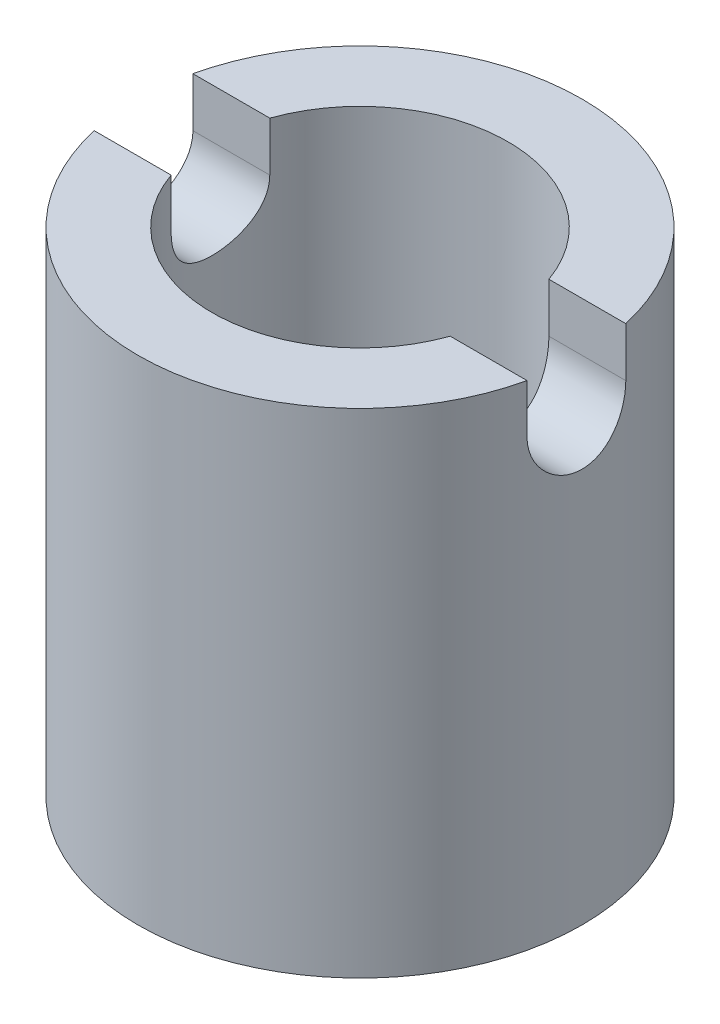
SolidWorks part; units mm, degrees
ref_plane "正面" through (0, 0, 0) normal (0, 0, 1) x (1, 0, 0)
ref_plane "平面" through (0, 0, 0) normal (0, 1, 0) x (1, 0, 0)
ref_plane "右側面" through (0, 0, 0) normal (1, 0, 0) x (0, 0, -1)
sketch "ｽｹｯﾁ1" plane through (0, 0, 0) normal (0, 1, 0) x (1, 0, 0)
  circle A0 centre (0, 0) radius 3
  circle A1 centre (0, 0) radius 4.5
  dimension "D1" = 6
  dimension "D2" = 1.5
extrude "ﾎﾞｽ - 押し出し1" add sketch "ｽｹｯﾁ1" along normal blind 9
sketch "ｽｹｯﾁ2" plane through (0, 0, 0) normal (1, 0, 0) x (0, 0, -1)
  line L0 (0, 0) -> (0, 9) construction
  circle A0 centre (0, 9) radius 1
  dimension "D2" = 2
  dimension "D1" = 9
extrude "ｶｯﾄ - 押し出し3" cut sketch "ｽｹｯﾁ2" against normal through all both and the other way through all
sketch "ｽｹｯﾁ3" plane through (0, 9, 0) normal (0, 1, 0) x (1, 0, 0)
  line L0 (-2.8284, -1) -> (-4.3875, -1) construction
  line L1 (4.3875, -1) -> (2.8284, -1) construction
  line L2 (2.8284, 1) -> (4.3875, 1) construction
  line L3 (-4.3875, 1) -> (-2.8284, 1) construction
  line L4 (-2.8284, -1) -> (-4.3875, -1)
  line L5 (4.3875, -1) -> (2.8284, -1)
  line L6 (2.8284, 1) -> (4.3875, 1)
  line L7 (-4.3875, 1) -> (-2.8284, 1)
  arc A0 (-4.3875, -1) -> (4.3875, -1) centre (0, 0) ccw construction
  arc A1 (-2.8284, -1) -> (2.8284, -1) centre (0, 0) ccw construction
  arc A2 (4.3875, 1) -> (-4.3875, 1) centre (0, 0) ccw construction
  arc A3 (2.8284, 1) -> (-2.8284, 1) centre (0, 0) ccw construction
  arc A4 (-4.3875, -1) -> (4.3875, -1) centre (0, 0) ccw
  arc A5 (-2.8284, -1) -> (2.8284, -1) centre (0, 0) ccw
  arc A6 (4.3875, 1) -> (-4.3875, 1) centre (0, 0) ccw
  arc A7 (2.8284, 1) -> (-2.8284, 1) centre (0, 0) ccw
extrude "ﾎﾞｽ - 押し出し2" add sketch "ｽｹｯﾁ3" along normal blind 1
